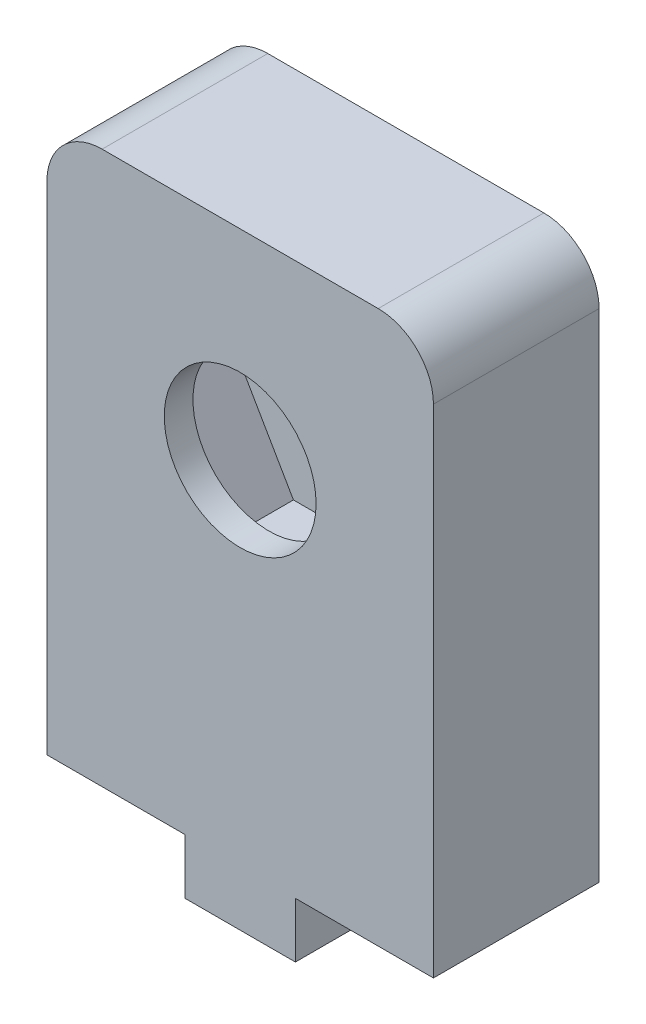
SolidWorks part; units mm, degrees
ref_plane "Front Plane" through (0, 0, 0) normal (0, 0, 1) x (1, 0, 0)
ref_plane "Top Plane" through (0, 0, 0) normal (0, 1, 0) x (1, 0, 0)
ref_plane "Right Plane" through (0, 0, 0) normal (1, 0, 0) x (0, 0, -1)
sketch "Sketch1" plane through (0, 0, 0) normal (0, 0, 1) x (1, 0, 0)
  line L0 (-1, -6.375) -> (-1, -7.375)
  line L1 (-2.5, 3.625) -> (2.5, 3.625)
  line L2 (-3.5, 2.625) -> (-3.5, -6.375)
  line L3 (-3.5, -6.375) -> (-1, -6.375)
  line L4 (3.5, 2.625) -> (3.5, -6.375)
  line L7 (3.0311, 0) -> (1.5155, 2.625) construction
  line L8 (1.5155, 2.625) -> (-1.5155, 2.625) construction
  line L9 (-1.5155, 2.625) -> (-3.0311, 0) construction
  line L10 (-3.0311, 0) -> (-1.5155, -2.625) construction
  line L11 (-1.5155, -2.625) -> (1.5155, -2.625) construction
  line L12 (1.5155, -2.625) -> (3.0311, 0) construction
  line L13 (-1, -7.375) -> (1, -7.375)
  line L14 (1, -7.375) -> (1, -6.375)
  line L15 (1, -6.375) -> (3.5, -6.375)
  arc A0 (3.5, 2.625) -> (2.5, 3.625) centre (2.5, 2.625) ccw
  arc A1 (-2.5, 3.625) -> (-3.5, 2.625) centre (-2.5, 2.625) ccw
  circle A2 centre (0, 0) radius 2.625 construction
  circle A3 centre (0, 0) radius 1.375
  point P0 (0, 0)
  point P2 (0, 0)
  point P4 (0, 0)
  point P13 (0, 0)
  point P25 (0, 0)
  point P27 (0, 0)
  point P28 (0, 0)
  point P29 (0, 0)
  point P32 (0, 3.625)
  dimension "D3" = 1
  dimension "D7" = 2.75
  dimension "D1" = 1
  dimension "D2" = 10
  dimension "D4" = 5.25
  dimension "D5" = 2
  dimension "D6" = 1
  dimension "D8" = 7
extrude "Boss-Extrude1" add sketch "Sketch1" along normal blind 3
ref_plane "Plane1" through (0, 0, 1.5) normal (0, 0, 1) x (1, 0, 0)
sketch "Sketch2" plane through (0, 0, 1.5) normal (0, 0, 1) x (1, 0, 0)
  line L0 (-1.5155, -2.625) -> (1.5155, -2.625) construction
  line L1 (-3.0311, 0) -> (-1.5155, -2.625) construction
  line L2 (-1.5155, 2.625) -> (-3.0311, 0) construction
  line L3 (1.5155, 2.625) -> (-1.5155, 2.625) construction
  line L4 (1.5155, -2.625) -> (3.0311, 0) construction
  line L5 (3.0311, 0) -> (1.5155, 2.625) construction
  line L6 (-1.5155, -2.625) -> (1.5155, -2.625)
  line L7 (-3.0311, 0) -> (-1.5155, -2.625)
  line L8 (-1.5155, 2.625) -> (-3.0311, 0)
  line L9 (1.5155, 2.625) -> (-1.5155, 2.625)
  line L10 (1.5155, -2.625) -> (3.0311, 0)
  line L11 (3.0311, 0) -> (1.5155, 2.625)
extrude "Cut-Extrude1" cut sketch "Sketch2" against normal mid plane 1.96
